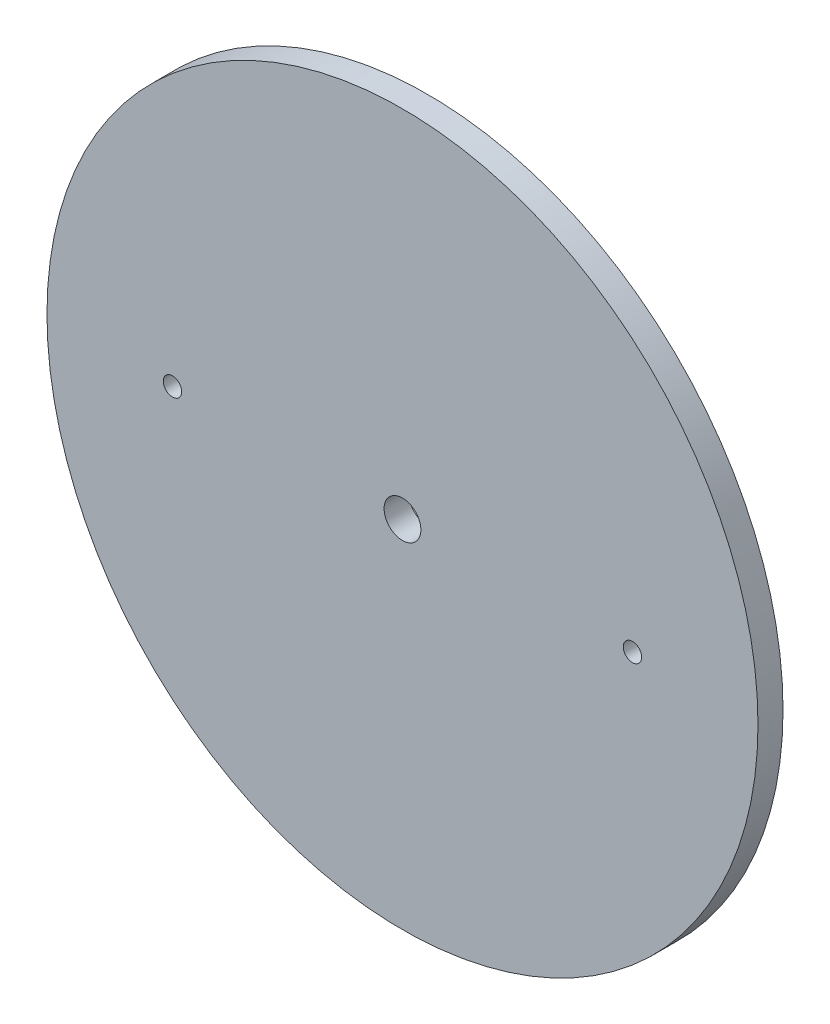
SolidWorks part; units mm, degrees
material "1060 Alloy"
ref_plane "Front Plane" through (0, 0, 0) normal (0, 0, 1) x (1, 0, 0)
ref_plane "Top Plane" through (0, 0, 0) normal (0, 1, 0) x (1, 0, 0)
ref_plane "Right Plane" through (0, 0, 0) normal (1, 0, 0) x (0, 0, -1)
ref_plane "Plane1" through (0, 0, -5) normal (0, 0, -1) x (-1, 0, 0)
sketch "Sketch1" plane through (0, 0, -5) normal (0, 0, -1) x (-1, 0, 0)
  circle A0 centre (45.9318, 0) radius 1.8373
  circle A1 centre (-45.9318, 0) radius 1.8373
  circle A2 centre (0, 0) radius 3.6745
  circle A3 centre (0, 0) radius 71
  dimension "D1" = 142
extrude "Boss-Extrude1" add sketch "Sketch1" against normal blind 5
